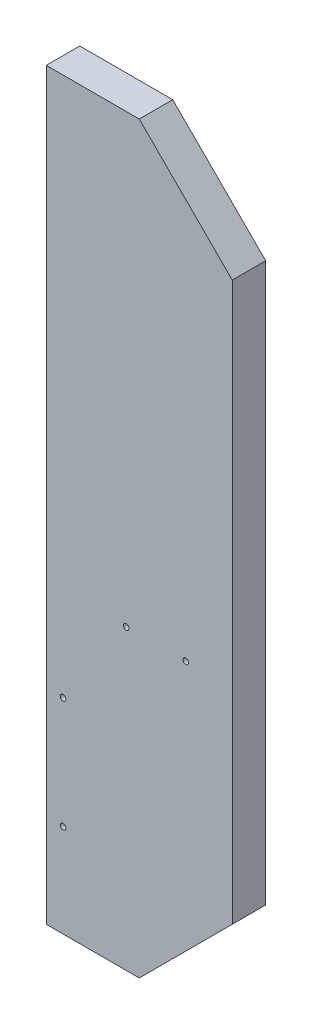
SolidWorks part; units mm, degrees
material "Faia"
ref_plane "Plano frontal" through (0, 0, 0) normal (0, 0, 1) x (1, 0, 0)
ref_plane "Plano superior" through (0, 0, 0) normal (0, 1, 0) x (1, 0, 0)
ref_plane "Plano direito" through (0, 0, 0) normal (1, 0, 0) x (0, 0, -1)
sketch "Esboço6" plane through (0, 0, 0) normal (0, 0, 1) x (1, 0, 0)
  line L1 (0, 0) -> (100, 0)
  line L2 (0, 0) -> (0, 400)
  line L3 (0, 400) -> (100, 400)
  line L4 (100, 0) -> (100, 400)
  dimension "D1" = 100
  dimension "D2" = 400
extrude "Ressalto-extrusão2" add sketch "Esboço6" along normal blind 18 separate body
sketch "Esboço7" plane through (0, 0, 18) normal (0, 0, 1) x (1, 0, 0)
  line L0 (50, 0) -> (100, 50)
  line L1 (0, 0) -> (100, 0) construction
  line L2 (100, 0) -> (100, 400) construction
  line L3 (50, 400) -> (100, 350)
  line L4 (50, 0) -> (100, 0)
  line L5 (100, 0) -> (100, 50)
  line L6 (100, 350) -> (100, 400)
  line L7 (0, 400) -> (0, 0)
  line L8 (0, 0) -> (100, 0)
  line L9 (100, 0) -> (100, 400)
  line L10 (100, 400) -> (0, 400)
  line L13 (100, 50) -> (100, 350)
  line L15 (100, 400) -> (50, 400)
  line L16 (50, 0) -> (50, 400) construction
  line L17 (100, 400) -> (0, 400) construction
  line M8 (0, 0) -> (100, 0)
  line M9 (100, 0) -> (100, 400)
  line M10 (100, 400) -> (0, 400)
  dimension "D1" = 0
  dimension "D2" = 45
  dimension "D3" = 45
extrude "Corte-extrusão2" cut sketch "Esboço7" against normal through all contours L3 M10 M9 | L0 M8 M9
sketch "Esboço8" plane through (0, 0, 0) normal (0, 0, -1) x (-1, 0, 0)
  line L0 (0, 0) -> (0, 160) construction
  line L1 (0, 400) -> (0, 0) construction
  line L2 (0, 160) -> (-100, 160) construction
  line L3 (-100, 50) -> (-100, 350) construction
  line L4 (0, 0) -> (-18, 0) construction
  line L5 (0, 0) -> (-50, 0) construction
  line L6 (-9, 0) -> (-9, 160) construction
  circle A0 centre (-75, 160) radius 1.5
  circle A1 centre (-43, 160) radius 1.5
  circle A2 centre (-9, 50) radius 1.5
  circle A3 centre (-9, 110) radius 1.5
  dimension "D1" = 3
  dimension "D4" = 50
  dimension "D2" = 25
  dimension "D3" = 43
  dimension "40" = 50
  dimension "D5" = 9
  dimension "D6" = 160
extrude "Corte-extrusão3" cut sketch "Esboço8" against normal through all
